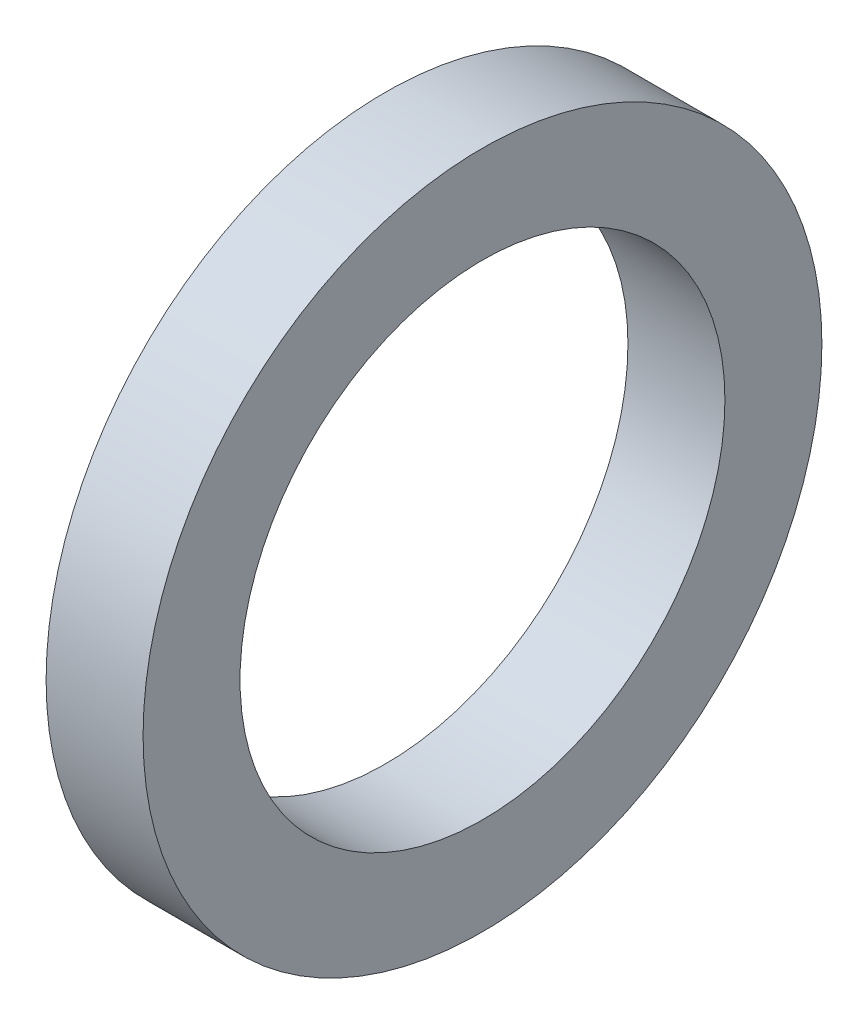
SolidWorks part; units mm, degrees
material "Nylon 101"
ref_plane "Front Plane" through (0, 0, 0) normal (0, 0, 1) x (1, 0, 0)
ref_plane "Top Plane" through (0, 0, 0) normal (0, 1, 0) x (1, 0, 0)
ref_plane "Right Plane" through (0, 0, 0) normal (1, 0, 0) x (0, 0, -1)
sketch "Sketch1" plane through (0, 0, 0) normal (1, 0, 0) x (0, 0, -1)
  line L7 (0, 7.3323) -> (-6.35, 3.6662) construction
  line L8 (-6.35, 3.6662) -> (-6.35, -3.6662) construction
  line L9 (-6.35, -3.6662) -> (0, -7.3323) construction
  line L10 (0, -7.3323) -> (6.35, -3.6662) construction
  line L11 (6.35, -3.6662) -> (6.35, 3.6662) construction
  line L12 (6.35, 3.6662) -> (0, 7.3323) construction
  circle A1 centre (0, 0) radius 11.1125
  circle A2 centre (0, 0) radius 6.35 construction
  circle A3 centre (0, 0) radius 7.9375
  dimension "D1" = 12.7
  dimension "D2" = 22.225
  dimension "D3" = 15.875
extrude "Boss-Extrude1" add sketch "Sketch1" along normal blind 3.175 contours A1
